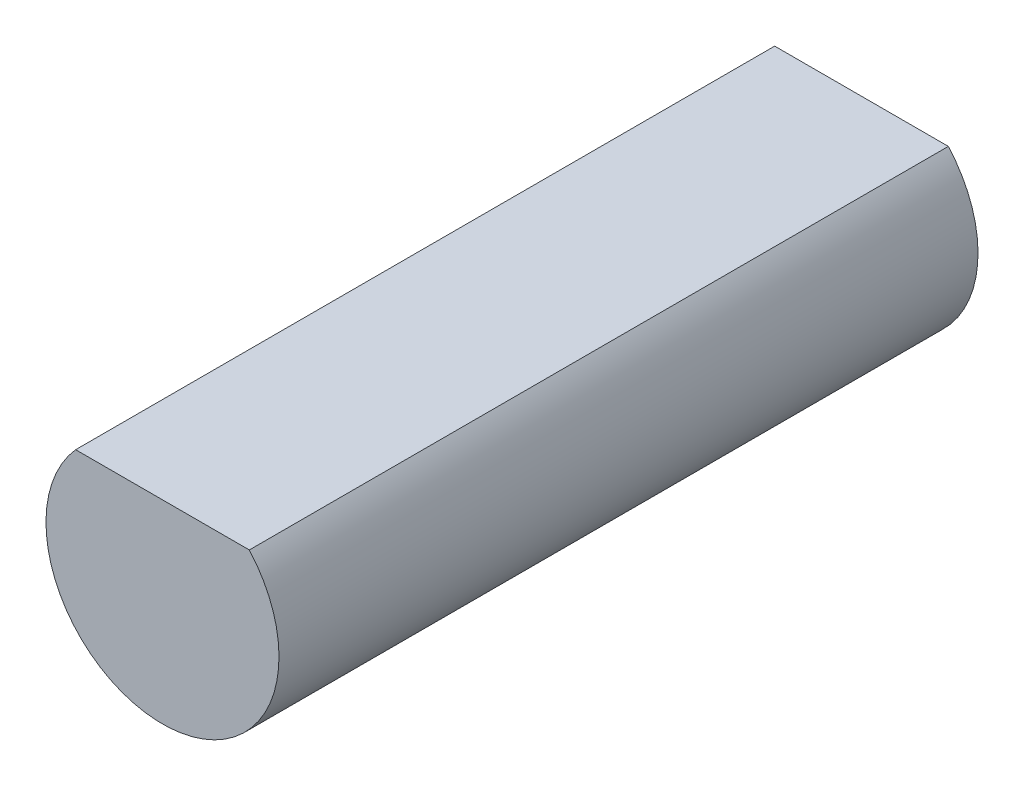
SolidWorks part; units mm, degrees
ref_plane "Front Plane" through (0, 0, 0) normal (0, 0, 1) x (1, 0, 0)
ref_plane "Top Plane" through (0, 0, 0) normal (0, 1, 0) x (1, 0, 0)
ref_plane "Right Plane" through (0, 0, 0) normal (1, 0, 0) x (0, 0, -1)
sketch "Sketch1" plane through (0, 0, 0) normal (0, 0, 1) x (1, 0, 0)
  line L0 (-1.118, 1) -> (1.118, 1)
  arc A0 (-1.118, 1) -> (1.118, 1) centre (0, 0) ccw
  dimension "D1" = 1.5
  dimension "D2" = 1
extrude "Boss-Extrude1" add sketch "Sketch1" along normal blind 9
